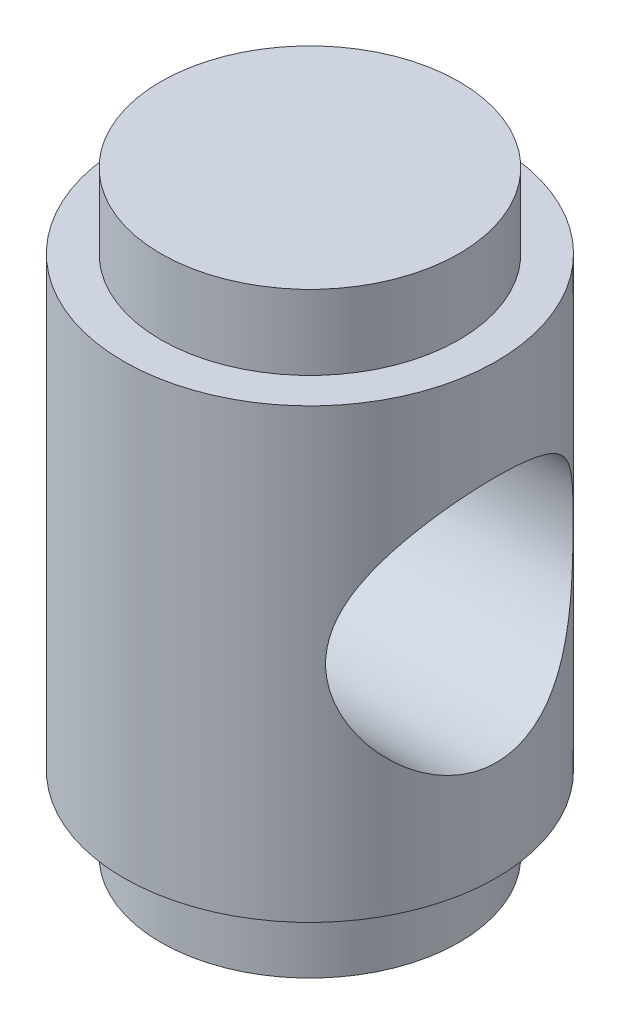
SolidWorks part; units mm, degrees
ref_plane "Alzado" through (0, 0, 0) normal (0, 0, 1) x (1, 0, 0)
ref_plane "Planta" through (0, 0, 0) normal (0, 1, 0) x (1, 0, 0)
ref_plane "Vista lateral" through (0, 0, 0) normal (1, 0, 0) x (0, 0, -1)
sketch "Sketch1" plane through (0, 0, 0) normal (0, 0, 1) x (1, 0, 0)
  line L0 (20, -30) -> (20, -40)
  line L4 (25, -30) -> (25, 30)
  line L7 (0, 40) -> (20, 40)
  line L8 (20, 30) -> (20, 40)
  line L9 (0, -40) -> (20, -40)
  line L12 (0, 40) -> (0, -40)
  line L13 (20, 30) -> (25, 30)
  line L14 (25, -30) -> (20, -30)
  dimension "D2" = 10
  dimension "D3" = 20
revolve "Revolve1" add sketch "Sketch1" angle 360 about L12
hole_wizard "Ø1.0mm Dowel Hole1" positions "Sketch2" profile "Sketch3" hole size "Ø1.0" standard "ISO"
sketch "Sketch2" plane through (0, 0, 0) normal (1, 0, 0) x (0, 0, -1)
  point P0 (0, 0)
sketch "Sketch3" plane through (0, 0, 0) normal (0, 1, 0) x (0, 0, 1)
  line L0 (0, 0) -> (0, 25)
  line L1 (0, 25) -> (16.6, 25)
  line L2 (16.6, 25) -> (16.6, 0)
  line L5 (16.6, 0) -> (0, 0)
  line L11 (0, -6.35) -> (0, 107.95) construction
  dimension "Thru Hole Dia." = 33.2
  dimension "Thru Hole Depth" = 25
hole_wizard "Ø25.0mm Dowel Hole2" positions "Sketch4" profile "Sketch5" hole size "Ø25.0" standard "ISO" end condition through all
sketch "Sketch4" plane through (0, 0, 0) normal (1, 0, 0) x (0, 0, -1)
  point P0 (0, 0)
sketch "Sketch5" plane through (0, 0, 0) normal (0, 1, 0) x (0, 0, -1)
  line L0 (0, 0) -> (0, 25)
  line L1 (0, 25) -> (16.6, 25)
  line L2 (16.6, 25) -> (16.6, 0)
  line L5 (16.6, 0) -> (0, 0)
  line L11 (0, -6.35) -> (0, 107.95) construction
  dimension "Thru Hole Dia." = 33.2
  dimension "Thru Hole Depth" = 25
